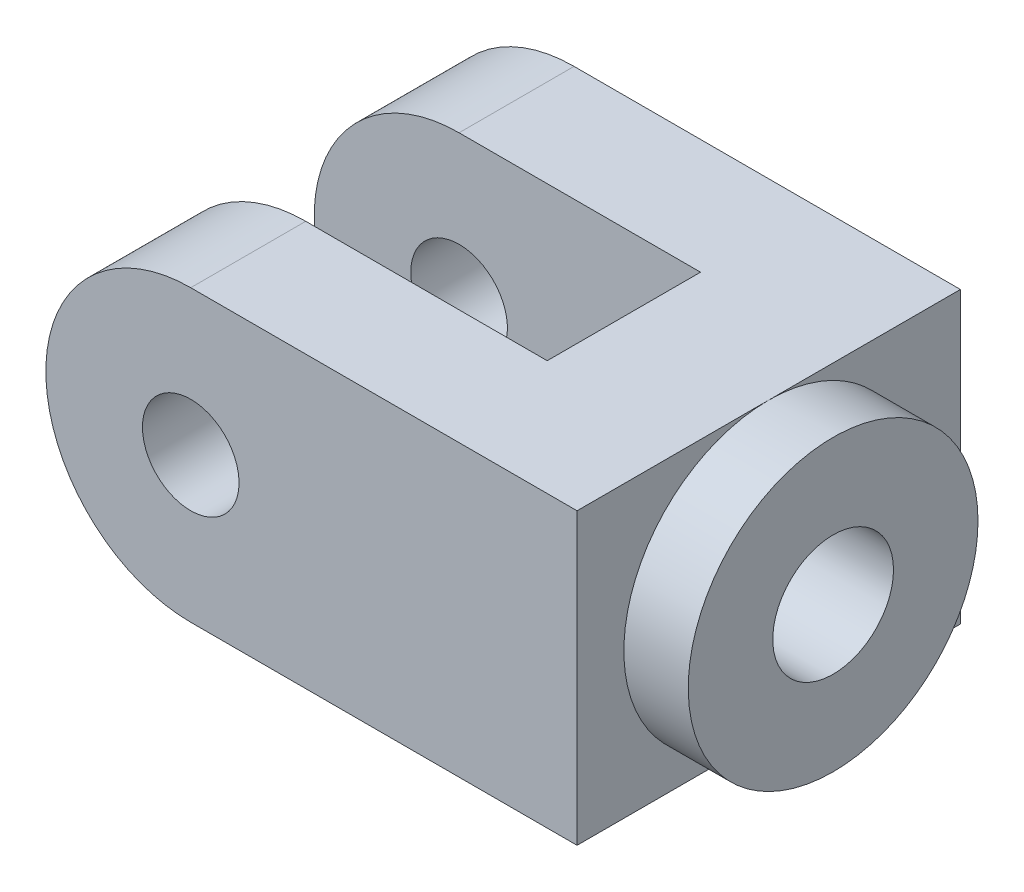
SolidWorks part; units mm, degrees
ref_plane "Front Plane" through (0, 0, 0) normal (0, 0, 1) x (1, 0, 0)
ref_plane "Top Plane" through (0, 0, 0) normal (0, 1, 0) x (1, 0, 0)
ref_plane "Right Plane" through (0, 0, 0) normal (1, 0, 0) x (0, 0, -1)
sketch "Sketch1" plane through (0, 0, 0) normal (0, 0, 1) x (1, 0, 0)
  line L1 (66, -36) -> (-66, -36)
  line L2 (66, -36) -> (66, 36)
  line L3 (66, 36) -> (-66, 36)
  line L4 (-66, -36) -> (-66, 36)
  line L5 (66, -36) -> (-66, 36) construction
  line L6 (66, 36) -> (-66, -36) construction
  point P0 (0, 0)
  dimension "D1" = 132
  dimension "D2" = 72
extrude "Boss-Extrude1" add sketch "Sketch1" along normal mid plane 95.25
sketch "Sketch2" plane through (0, 0, 47.625) normal (0, 0, 1) x (1, 0, 0)
  line L0 (66, 36) -> (-66, 36) construction
  line L1 (-66, -36) -> (66, -36) construction
  line L2 (-66, 36) -> (-66, -36) construction
  arc A0 (-30, 36) -> (-30, -36) centre (-30, 0) ccw
  dimension "D1" = 36
extrude "Cut-Extrude2" cut sketch "Sketch2" against normal through all and the other way through all flip side to cut
sketch "Sketch3" plane through (0, 36, 0) normal (0, 1, 0) x (1, 0, 0)
  line L0 (-66, 47.625) -> (-66, -47.625) construction
  line L1 (30, 19.055) -> (-66, 19.055)
  line L2 (30, 19.055) -> (30, -19.045)
  line L3 (30, -19.045) -> (-66, -19.045)
  line L4 (-66, 19.055) -> (-66, -19.045)
  line L5 (-66, -47.625) -> (-30, -47.625) construction
  line L6 (-30, -47.625) -> (-30, 47.625) construction
  dimension "D1" = 38.1
  dimension "D2" = 28.58
  dimension "D3" = 60
extrude "Cut-Extrude3" cut sketch "Sketch3" against normal through all
sketch "Sketch4" plane through (66, 0, 0) normal (1, 0, 0) x (0, 0, -1)
  circle A0 centre (0, 0) radius 15
  dimension "D1" = 30
extrude "Cut-Extrude4" cut sketch "Sketch4" against normal through all
sketch "Sketch5" plane through (66, 0, 0) normal (1, 0, 0) x (0, 0, -1)
  circle A0 centre (0, 0) radius 36
  circle A1 centre (0, 0) radius 15 construction
  circle A2 centre (0, 0) radius 15
extrude "Boss-Extrude2" add sketch "Sketch5" along normal blind 16
sketch "Sketch6" plane through (0, 0, -47.625) normal (0, 0, -1) x (-1, 0, 0)
  circle A0 centre (30, 0) radius 12
  dimension "D1" = 24
extrude "Cut-Extrude5" cut sketch "Sketch6" against normal through all
